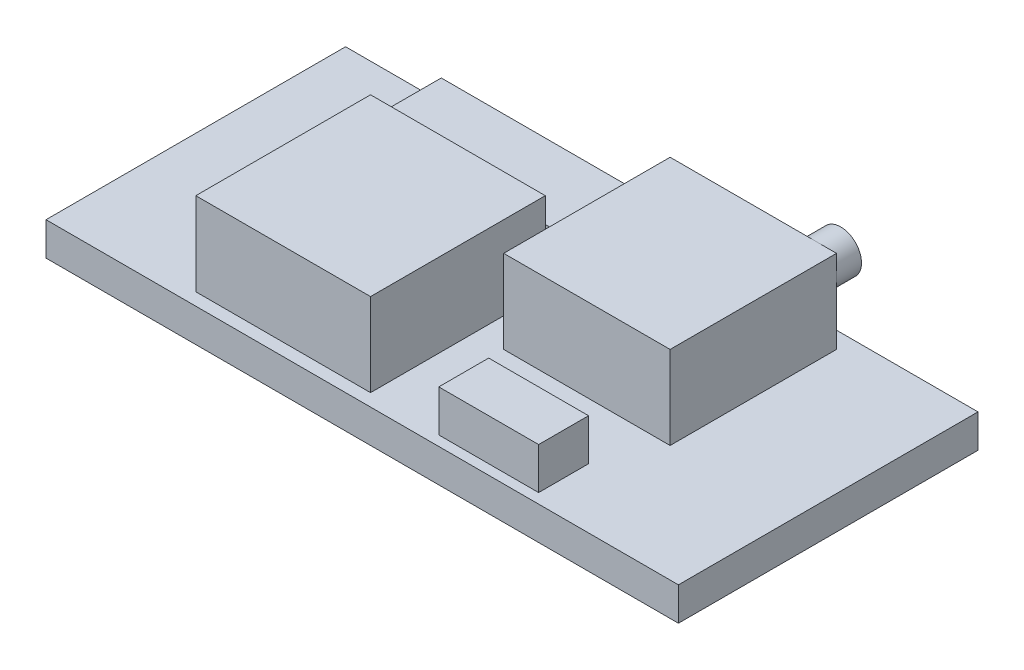
SolidWorks part; units mm, degrees
ref_plane "Front Plane" through (0, 0, 0) normal (0, 0, 1) x (1, 0, 0)
ref_plane "Top Plane" through (0, 0, 0) normal (0, 1, 0) x (1, 0, 0)
ref_plane "Right Plane" through (0, 0, 0) normal (1, 0, 0) x (0, 0, -1)
sketch "Sketch1" plane through (0, 0, 0) normal (0, 1, 0) x (1, 0, 0)
  line L1 (19, -9) -> (-19, -9)
  line L2 (19, -9) -> (19, 9)
  line L3 (19, 9) -> (-19, 9)
  line L4 (-19, -9) -> (-19, 9)
  line L5 (19, -9) -> (-19, 9) construction
  line L6 (19, 9) -> (-19, -9) construction
  point P0 (0, 0)
  dimension "D1" = 18
  dimension "D2" = 38
extrude "Boss-Extrude1" add sketch "Sketch1" along normal blind 2
sketch "Sketch2" plane through (0, 2, 0) normal (0, 1, 0) x (1, 0, 0)
  line L1 (4, -5.4) -> (10, -5.4)
  line L2 (4, -5.4) -> (4, -8.4)
  line L3 (4, -8.4) -> (10, -8.4)
  line L4 (10, -5.4) -> (10, -8.4)
  line L5 (19, -9) -> (19, 9) construction
  line L6 (-19, -9) -> (19, -9) construction
  line L7 (19, 9) -> (-19, 9) construction
  line L8 (-12, 7.75) -> (-1, 7.75)
  line L9 (-12, 7.75) -> (-12, 3.25)
  line L10 (-12, 3.25) -> (-1, 3.25)
  line L11 (-1, 7.75) -> (-1, 3.25)
  line L12 (-19, 9) -> (-19, -9) construction
  point P4 (10, -6.9)
  point P6 (7, -5.4)
  point P14 (-12, 5.5)
  point P17 (-6.5, 3.25)
  dimension "D1" = 6
  dimension "D2" = 3
  dimension "D3" = 2.1
  dimension "D4" = 12
  dimension "D5" = 11
  dimension "D6" = 4.5
  dimension "D7" = 3.5
  dimension "D8" = 12.5
extrude "Boss-Extrude2" add sketch "Sketch2" along normal blind 2.5
sketch "Sketch3" plane through (0, 2, 0) normal (0, 1, 0) x (1, 0, 0)
  line L0 (19, 9) -> (-19, 9) construction
  line L1 (-10.75, 2.25) -> (-0.25, 2.25)
  line L2 (-10.75, 2.25) -> (-10.75, -8.25)
  line L3 (-10.75, -8.25) -> (-0.25, -8.25)
  line L4 (-0.25, 2.25) -> (-0.25, -8.25)
  line L5 (1.5, 8) -> (11.5, 8)
  line L6 (1.5, 8) -> (1.5, -2)
  line L7 (1.5, -2) -> (11.5, -2)
  line L8 (11.5, 8) -> (11.5, -2)
  line L9 (19, -9) -> (19, 9) construction
  line L10 (-19, 9) -> (-19, -9) construction
  line L11 (-19, -9) -> (19, -9) construction
  point P8 (11.5, 3)
  point P11 (6.5, 8)
  point P14 (-5.5, -8.25)
  point P17 (-10.75, -3)
  dimension "D1" = 10.5
  dimension "D2" = 10
  dimension "D3" = 6
  dimension "D4" = 12.5
  dimension "D5" = 13.5
  dimension "D6" = 6
extrude "Boss-Extrude3" add sketch "Sketch3" along normal blind 5
sketch "Sketch4" plane through (0, 0, -8) normal (0, 0, -1) x (-1, 0, 0)
  line L0 (-11.5, 7) -> (-1.5, 7) construction
  line L1 (-11.5, 7) -> (-11.5, 2) construction
  circle A0 centre (-10.25, 5.75) radius 1.25
  point P2 (-9.0822, 4.8444)
  dimension "D1" = 2.5
extrude "Boss-Extrude4" add sketch "Sketch4" along normal blind 1.5
